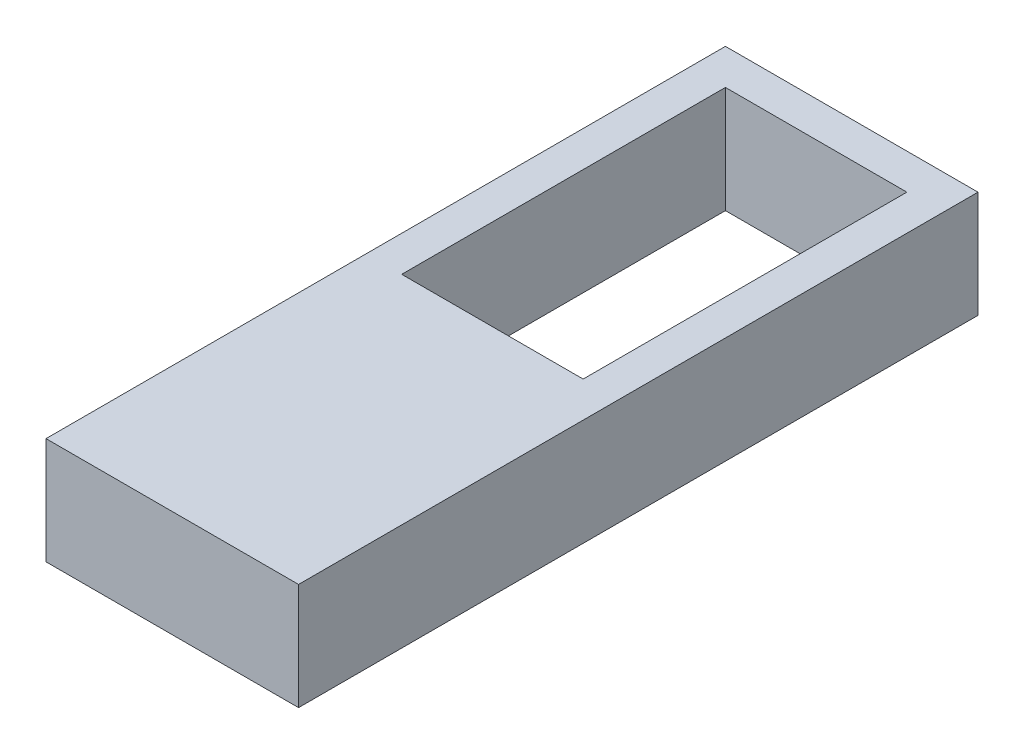
SolidWorks part; units mm, degrees
ref_plane "Front Plane" through (0, 0, 0) normal (0, 0, 1) x (1, 0, 0)
ref_plane "Top Plane" through (0, 0, 0) normal (0, 1, 0) x (1, 0, 0)
ref_plane "Right Plane" through (0, 0, 0) normal (1, 0, 0) x (0, 0, -1)
sketch "Sketch1" plane through (0, 0, 0) normal (0, 1, 0) x (1, 0, 0)
  line L0 (-1, 1) -> (6.1, 1)
  line L1 (0, 0) -> (5.1, 0)
  line L2 (0, 0) -> (0, -9.1)
  line L3 (0, -9.1) -> (5.1, -9.1)
  line L4 (5.1, 0) -> (5.1, -9.1)
  line L5 (6.1, 1) -> (6.1, -10.1)
  line L6 (-1, -10.1) -> (6.1, -10.1)
  line L7 (-1, 1) -> (-1, -10.1)
  line L9 (-1, -10.1) -> (6.1, -10.1)
  line L10 (-1, -10.1) -> (-1, -18.1)
  line L11 (-1, -18.1) -> (6.1, -18.1)
  line L12 (6.1, -10.1) -> (6.1, -18.1)
  dimension "D1" = 5.1
  dimension "D2" = 9.1
  dimension "D4" = 8
  dimension "D3" = 1
extrude "Boss-Extrude1" add sketch "Sketch1" along normal blind 3 contours L0 L7 L6 L5 L1 L4 L3 L2 | L12 L6 L10 L11
